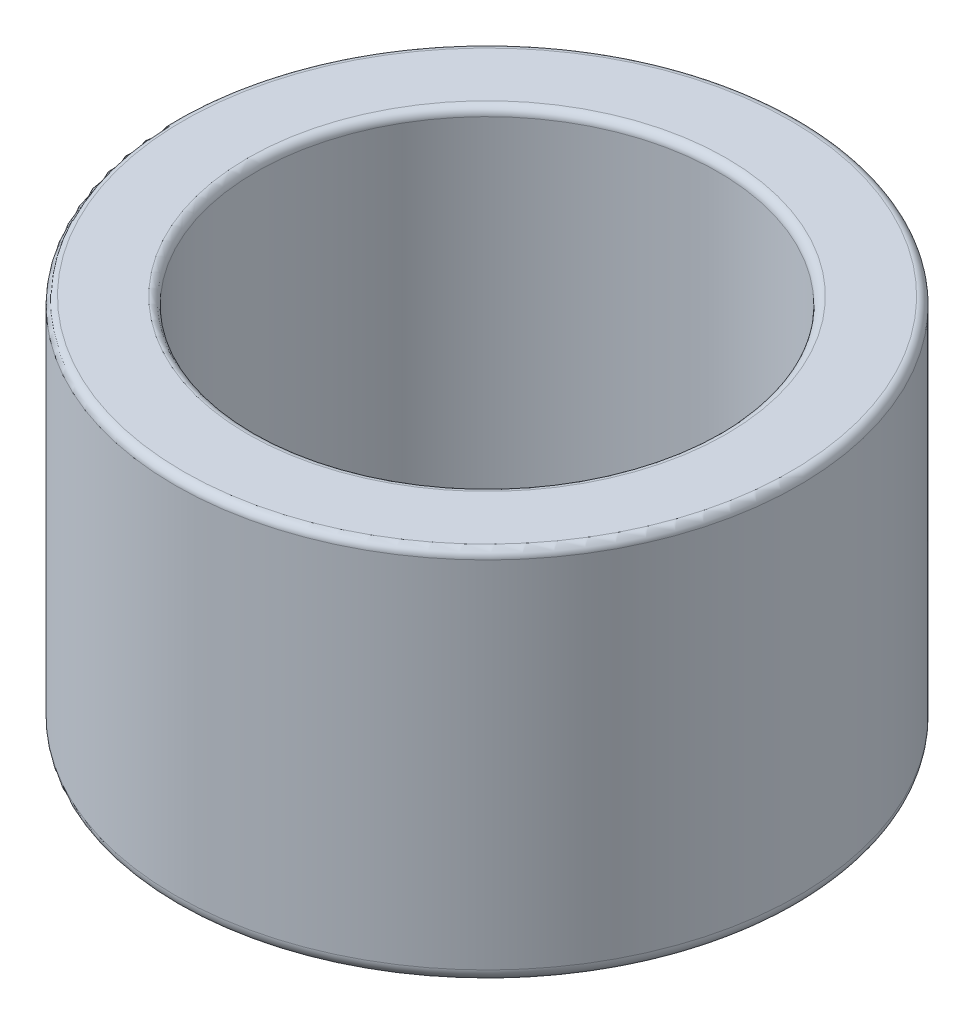
SolidWorks part; units mm, degrees
ref_plane "Front Plane" through (0, 0, 0) normal (0, 0, 1) x (1, 0, 0)
ref_plane "Top Plane" through (0, 0, 0) normal (0, 1, 0) x (1, 0, 0)
ref_plane "Right Plane" through (0, 0, 0) normal (1, 0, 0) x (0, 0, -1)
sketch "Sketch1" plane through (0, 0, 0) normal (0, 1, 0) x (1, 0, 0)
  circle A0 centre (0, 0) radius 8.5944
  circle A1 centre (0, 0) radius 11.5944
  dimension "D1" = 17.1887
  dimension "D2" = 3
extrude "Boss-Extrude1" add sketch "Sketch1" along normal blind 14
fillet "Fillet1" radius 0.3 1 edges at (0, 14, 11.5944)
fillet "Fillet5" radius 0.3 1 edges at (0, 14, 8.5944)
fillet "Fillet6" radius 0.5 1 edges at (0, 0, 11.5944)
fillet "Fillet7" radius 0.5 1 edges at (0, 0, 8.5944)
